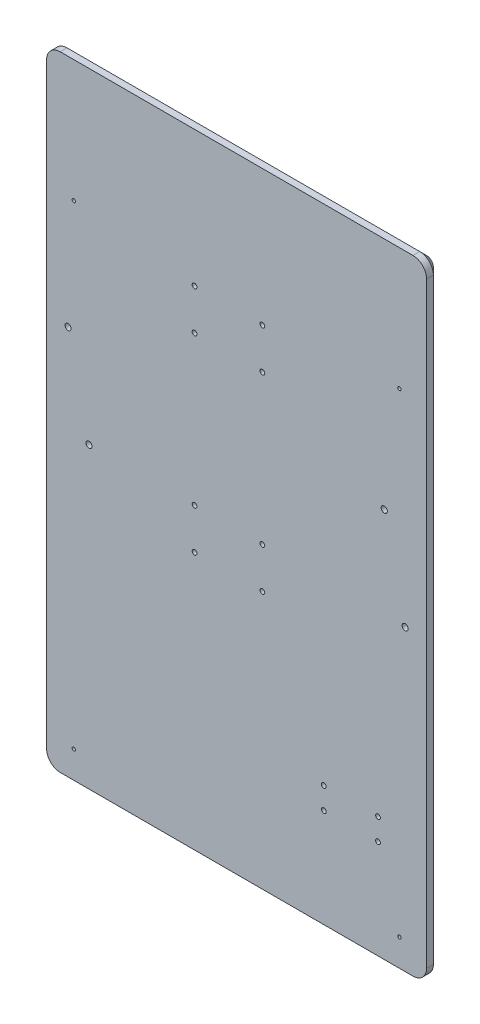
SolidWorks part; units mm, degrees
material "Oak"
ref_plane "Front Plane" through (0, 0, 0) normal (0, 0, 1) x (1, 0, 0)
ref_plane "Top Plane" through (0, 0, 0) normal (0, 1, 0) x (1, 0, 0)
ref_plane "Right Plane" through (0, 0, 0) normal (1, 0, 0) x (0, 0, -1)
sketch "Skica1" plane through (0, 0, 0) normal (0, 0, 1) x (1, 0, 0)
  line L1 (146, 234.9692) -> (-134, 234.9692)
  line L2 (146, 234.9692) -> (146, -225.0308)
  line L3 (146, -225.0308) -> (-134, -225.0308)
  line L4 (-134, 234.9692) -> (-134, -225.0308)
  line L6 (135, 67.0008) -> (135, -9.9992) construction
  line L8 (-5.6292, -199.0308) -> (0, -199.0308) construction
  dimension "D1" = 280
  dimension "D2" = 460
  dimension "D3" = 11
  dimension "D4" = 26
extrude "Přidat vysunutím1" add sketch "Skica1" along normal blind 10
sketch "Skica3" plane through (0, 0, 10) normal (0, 0, 1) x (1, 0, 0)
  circle A0 centre (25, 135) radius 1.75
  circle A1 centre (25, 105) radius 1.75
  circle A2 centre (-25, 135) radius 1.75
  circle A3 centre (-25, 105) radius 1.75
  circle A4 centre (-102.8, -5.1992) radius 2.25
  circle A5 centre (110.1867, -152.1089) radius 1.75
  circle A6 centre (110.2042, -136.1089) radius 1.75
  circle A7 centre (70.3095, -152.2142) radius 1.75
  circle A8 centre (70.2075, -136.2146) radius 1.75
  circle A9 centre (114.8, 62.2008) radius 2.25
  circle A10 centre (130.2, -5.1992) radius 2.25
  circle A11 centre (-118.2, 62.2008) radius 2.25
  circle A12 centre (25, -5) radius 1.75
  circle A13 centre (25, -35) radius 1.75
  circle A14 centre (-25, -35) radius 1.75
  circle A15 centre (-25, -5) radius 1.75
  dimension "D1" = 4.5
  dimension "D2" = 4.5
  dimension "D3" = 4.5
  dimension "D4" = 4.5
  dimension "D5" = 3.5
  dimension "D6" = 3.5
  dimension "D7" = 3.5
  dimension "D8" = 3.5
  dimension "D9" = 3.5
  dimension "D10" = 3.5
  dimension "D11" = 3.5
  dimension "D12" = 3.5
  dimension "D13" = 3.5
  dimension "D14" = 3.5
  dimension "D15" = 3.5
  dimension "D16" = 3.5
extrude "Odebrat vysunutím1" cut sketch "Skica3" against normal blind 10
sketch "Skica4" plane through (0, 0, 10) normal (0, 0, 1) x (1, 0, 0)
  line L0 (6, -225.0308) -> (6, -30.0308) construction
  line L1 (-134, -225.0308) -> (146, -225.0308) construction
  line L2 (-134, 234.9692) -> (-134, -225.0308) construction
  line L3 (126, 144.9692) -> (-114, 144.9692) construction
  line L4 (126, 144.9692) -> (126, -205.0308) construction
  line L5 (126, -205.0308) -> (-114, -205.0308) construction
  line L6 (-114, 144.9692) -> (-114, -205.0308) construction
  line L7 (126, 144.9692) -> (-114, -205.0308) construction
  line L8 (126, -205.0308) -> (-114, 144.9692) construction
  circle A0 centre (126, 144.9692) radius 1.25
  circle A1 centre (126, -205.0308) radius 1.25
  circle A2 centre (-114, -205.0308) radius 1.25
  circle A3 centre (-114, 144.9692) radius 1.25
  dimension "D1" = 2.5
  dimension "D2" = 2.5
  dimension "D3" = 2.5
  dimension "D4" = 2.5
  dimension "D5" = 20
  dimension "D6" = 20
  dimension "D7" = 350
extrude "Odebrat vysunutím2" cut sketch "Skica4" against normal blind 10
fillet "Zaoblit1" radius 10 4 edges at (-134, -225.0308, 5) (-134, 234.9692, 5) (146, 234.9692, 5) (146, -225.0308, 5)
chamfer "Zkosení1" distance 5 angle 45 8 edges at (6, -225.0308, 0) (143.0711, -222.1019, 0) (-131.0711, -222.1019, 0) (146, 4.9692, 0) (-134, 4.9692, 0) (143.0711, 232.0403, 0) (-131.0711, 232.0403, 0) (6, 234.9692, 0)
